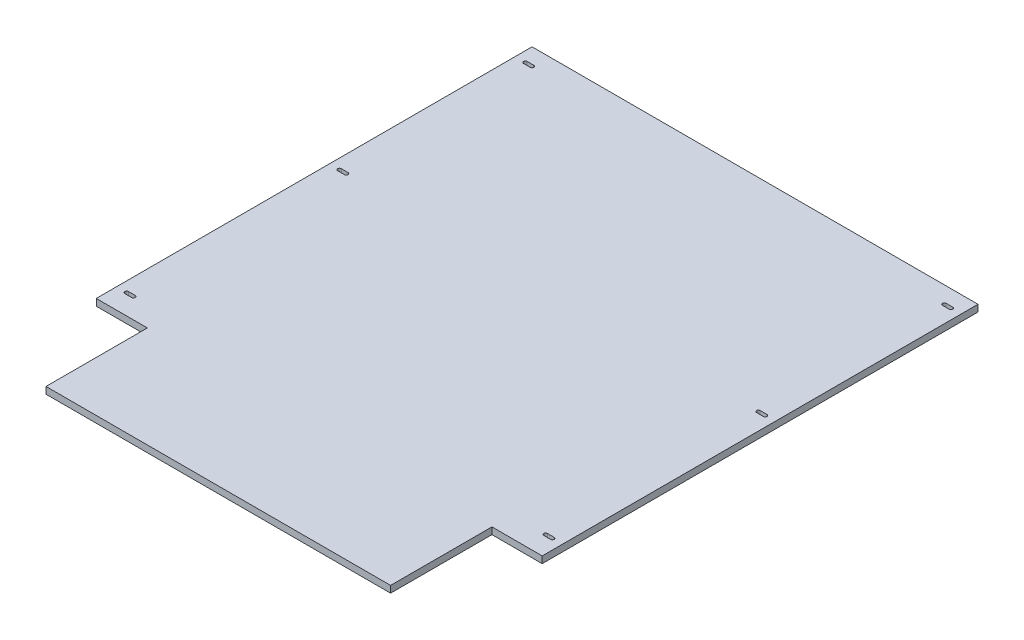
SolidWorks part; units mm, degrees
material "PE High Density"
ref_plane "Front" through (0, 0, 0) normal (0, 0, 1) x (1, 0, 0)
ref_plane "Top" through (0, 0, 0) normal (0, 1, 0) x (1, 0, 0)
ref_plane "Right" through (0, 0, 0) normal (1, 0, 0) x (0, 0, -1)
sketch "Sketch1" plane through (0, 0, 0) normal (0, 1, 0) x (1, 0, 0)
  line L0 (0, 0) -> (96.0438, 0)
  line L1 (96.0438, 0) -> (96.0438, -190.5)
  line L2 (96.0438, -190.5) -> (743.7437, -190.5)
  line L3 (743.7437, -190.5) -> (743.7437, 0)
  line L4 (743.7437, 0) -> (838.2, 0)
  line L5 (838.2, 0) -> (838.2, 819.15)
  line L6 (838.2, 819.15) -> (0, 819.15)
  line L7 (0, 819.15) -> (0, 0)
  line L8 (25.4, 0) -> (25.4, 819.15) construction
  line L9 (19.05, 38.1) -> (31.75, 38.1) construction
  line L10 (19.05, 41.4782) -> (31.75, 41.4782)
  line L11 (19.05, 34.7218) -> (31.75, 34.7218)
  line L12 (19.05, 438.15) -> (31.75, 438.15) construction
  line L13 (19.05, 441.5282) -> (31.75, 441.5282)
  line L14 (19.05, 434.7718) -> (31.75, 434.7718)
  line L15 (31.75, 787.4) -> (19.05, 787.4) construction
  line L16 (31.75, 784.0218) -> (19.05, 784.0218)
  line L17 (31.75, 790.7782) -> (19.05, 790.7782)
  line L18 (419.8937, 819.15) -> (419.8938, -190.5) construction
  line L19 (812.8, 787.4) -> (812.8, 438.15) construction
  line L20 (806.45, 787.4) -> (819.15, 787.4) construction
  line L21 (806.45, 784.0218) -> (819.15, 784.0218)
  line L22 (806.45, 790.7782) -> (819.15, 790.7782)
  line L23 (819.15, 438.15) -> (806.45, 438.15) construction
  line L24 (819.15, 441.5282) -> (806.45, 441.5282)
  line L25 (819.15, 434.7718) -> (806.45, 434.7718)
  line L26 (819.15, 38.1) -> (806.45, 38.1) construction
  line L27 (819.15, 41.4782) -> (806.45, 41.4782)
  line L28 (819.15, 34.7218) -> (806.45, 34.7218)
  line L29 (419.8938, -190.5) -> (419.8937, 819.15) construction
  line L30 (812.8, 438.15) -> (812.8, 38.1) construction
  arc A1 (19.05, 41.4782) -> (19.05, 34.7218) centre (19.05, 38.1) ccw
  arc A2 (31.75, 34.7218) -> (31.75, 41.4782) centre (31.75, 38.1) ccw
  arc A3 (19.05, 441.5282) -> (19.05, 434.7718) centre (19.05, 438.15) ccw
  arc A4 (31.75, 434.7718) -> (31.75, 441.5282) centre (31.75, 438.15) ccw
  arc A5 (31.75, 784.0218) -> (31.75, 790.7782) centre (31.75, 787.4) ccw
  arc A6 (19.05, 790.7782) -> (19.05, 784.0218) centre (19.05, 787.4) ccw
  arc A7 (806.45, 784.0218) -> (806.45, 790.7782) centre (806.45, 787.4) cw
  arc A8 (819.15, 790.7782) -> (819.15, 784.0218) centre (819.15, 787.4) cw
  arc A9 (819.15, 441.5282) -> (819.15, 434.7718) centre (819.15, 438.15) cw
  arc A10 (806.45, 434.7718) -> (806.45, 441.5282) centre (806.45, 438.15) cw
  arc A11 (819.15, 41.4782) -> (819.15, 34.7218) centre (819.15, 38.1) cw
  arc A12 (806.45, 34.7218) -> (806.45, 41.4782) centre (806.45, 38.1) cw
  point P13 (25.4, 38.1)
  point P20 (25.4, 438.15)
  point P27 (25.4, 787.4)
  point P38 (812.8, 787.4)
  point P45 (812.8, 438.15)
  point P52 (812.8, 38.1)
  dimension "D2" = 96.0438
  dimension "D3" = 819.15
  dimension "D4" = 25.4
  dimension "D5" = 6.7564
  dimension "D6" = 38.1
  dimension "D7" = 12.7
  dimension "D8" = 400.05
  dimension "D9" = 349.25
  dimension "D10" = 190.5
  dimension "D11" = 647.7
  dimension "D12" = 25.4
  dimension "D13" = 94.4562
extrude "Boss-Extrude1" add sketch "Sketch1" along normal blind 12.7
fillet "Fillet1" [suppressed] radius 6.604
fillet "Fillet2" [suppressed] radius 6.604
sketch "Sketch2" plane through (0, 12.7, 0) normal (0, 1, 0) x (1, 0, 0)
  line L0 (838.2, 0) -> (838.2, 819.15) construction
  line L1 (838.2, 0) -> (838.2, 819.15) construction
  line L3 (806.45, 438.15) -> (819.15, 438.15) construction
  line L5 (838.2, 483.87) -> (47.625, 483.87) construction
  line L6 (0, 819.15) -> (0, 0) construction
  circle A6 centre (47.625, 483.87) radius 12.7
  circle A7 centre (790.575, 483.87) radius 12.7
  dimension "D1" = 45.72
  dimension "D2" = 25.4
  dimension "D3" = 47.625
  dimension "D4" = 47.625
extrude "Cut-Extrude1" [suppressed] cut sketch "Sketch2" against normal through all
sketch "Sketch4" plane through (0, 0, 0) normal (0, -1, 0) x (1, 0, 0)
  line L0 (0, -819.15) -> (0, 0) construction
  line L3 (327.025, -527.05) -> (327.025, -549.275) construction
  line L4 (350.8375, -527.05) -> (350.8375, -549.275)
  line L5 (303.2125, -527.05) -> (303.2125, -549.275)
  line L7 (838.2, -819.15) -> (0, -819.15) construction
  line L8 (327.025, 0) -> (327.025, -22.225) construction
  line L9 (350.8375, 0) -> (350.8375, -22.225)
  line L10 (303.2125, 0) -> (303.2125, -22.225)
  circle A0 centre (327.025, -538.1625) radius 28.575 construction
  arc A2 (350.8375, -527.05) -> (303.2125, -527.05) centre (327.025, -527.05) ccw
  arc A3 (303.2125, -549.275) -> (350.8375, -549.275) centre (327.025, -549.275) ccw
  arc A4 (350.8375, 0) -> (303.2125, 0) centre (327.025, 0) ccw
  arc A5 (303.2125, -22.225) -> (350.8375, -22.225) centre (327.025, -22.225) ccw
  point P8 (327.025, -11.1125)
  point P12 (327.025, -538.1625)
  dimension "D2" = 57.15
  dimension "D1" = 327.025
  dimension "D3" = 527.05
  dimension "D4" = 47.625
  dimension "D5" = 22.225
  dimension "D6" = 280.9875
extrude "Cut-Extrude3" [suppressed] cut sketch "Sketch4" against normal through all
sketch "Sketch5" [suppressed] plane through (0, 0, 0) normal (0, -1, 0) x (1, 0, 0)
  line L0 (327.025, -22.225) -> (327.025, -527.05) construction
  line L1 (327.025, -466.725) -> (327.025, -82.55) construction
  line L2 (320.675, -466.725) -> (320.675, -82.55)
  line L3 (333.375, -466.725) -> (333.375, -82.55)
  arc A0 (320.675, -466.725) -> (333.375, -466.725) centre (327.025, -466.725) ccw
  arc A1 (333.375, -82.55) -> (320.675, -82.55) centre (327.025, -82.55) ccw
  point P6 (327.025, -274.6375)
  dimension "D1" = 384.175
  dimension "D2" = 12.7
extrude "Cut-Extrude4" [suppressed] cut sketch "Sketch5" against normal through all
sketch "Sketch6" [suppressed] plane through (0, 0, 0) normal (0, -1, 0) x (1, 0, 0)
  line L0 (327.025, -82.55) -> (327.025, -466.725) construction
  line L1 (327.025, -274.6375) -> (354.0125, -274.6375) construction
  line L2 (354.0125, -122.2375) -> (354.0125, -427.0375) construction
  line L3 (300.0375, -122.2375) -> (300.0375, -427.0375) construction
  circle A0 centre (354.0125, -274.6375) radius 3.3782
  circle A1 centre (354.0125, -427.0375) radius 3.3782
  circle A2 centre (354.0125, -122.2375) radius 3.3782
  circle A3 centre (300.0375, -427.0375) radius 3.3782
  circle A4 centre (300.0375, -274.6375) radius 3.3782
  circle A5 centre (300.0375, -122.2375) radius 3.3782
  dimension "D2" = 6.7564
  dimension "D1" = 26.9875
  dimension "D3" = 152.4
extrude "Cut-Extrude5" [suppressed] cut sketch "Sketch6" against normal through all
sketch "Sketch7" [suppressed] plane through (0, 0, 0) normal (0, -1, 0) x (1, 0, 0)
  line L0 (838.2, -6.604) -> (838.2, -812.546) construction
  line L1 (0, -812.546) -> (0, -6.604) construction
  line L2 (838.2, -6.604) -> (838.2, -812.546)
  line L3 (0, -812.546) -> (0, -6.604)
  line L4 (835.025, -6.604) -> (835.025, -812.546)
  line L5 (9.525, -812.546) -> (9.525, -6.604)
  line L6 (16.129, -819.15) -> (6.604, -819.15)
  line L7 (16.129, 0) -> (6.604, 0)
  line L8 (831.596, 0) -> (828.421, 0)
  line L9 (828.421, -819.15) -> (831.596, -819.15)
  arc A0 (838.2, -6.604) -> (831.596, 0) centre (831.596, -6.604) ccw construction
  arc A1 (831.596, -819.15) -> (838.2, -812.546) centre (831.596, -812.546) ccw construction
  arc A2 (0, -812.546) -> (6.604, -819.15) centre (6.604, -812.546) ccw construction
  arc A3 (6.604, 0) -> (0, -6.604) centre (6.604, -6.604) ccw construction
  arc A4 (838.2, -6.604) -> (831.596, 0) centre (831.596, -6.604) ccw
  arc A5 (831.596, -819.15) -> (838.2, -812.546) centre (831.596, -812.546) ccw
  arc A6 (0, -812.546) -> (6.604, -819.15) centre (6.604, -812.546) ccw
  arc A7 (6.604, 0) -> (0, -6.604) centre (6.604, -6.604) ccw
  arc A8 (835.025, -6.604) -> (828.421, 0) centre (828.421, -6.604) ccw
  arc A9 (828.421, -819.15) -> (835.025, -812.546) centre (828.421, -812.546) ccw
  arc A10 (16.129, 0) -> (9.525, -6.604) centre (16.129, -6.604) ccw
  arc A11 (9.525, -812.546) -> (16.129, -819.15) centre (16.129, -812.546) ccw
  dimension "D2" = 3.175
  dimension "D4" = 9.525
  dimension "D1" = 2
  dimension "D3" = 2
extrude "Cut-Extrude6" [suppressed] cut sketch "Sketch7" against normal through all contours A9 L9 A5 L2 A4 L8 A8 L4 | A11 L5 A10 L7 A7 L3 A6 L6
